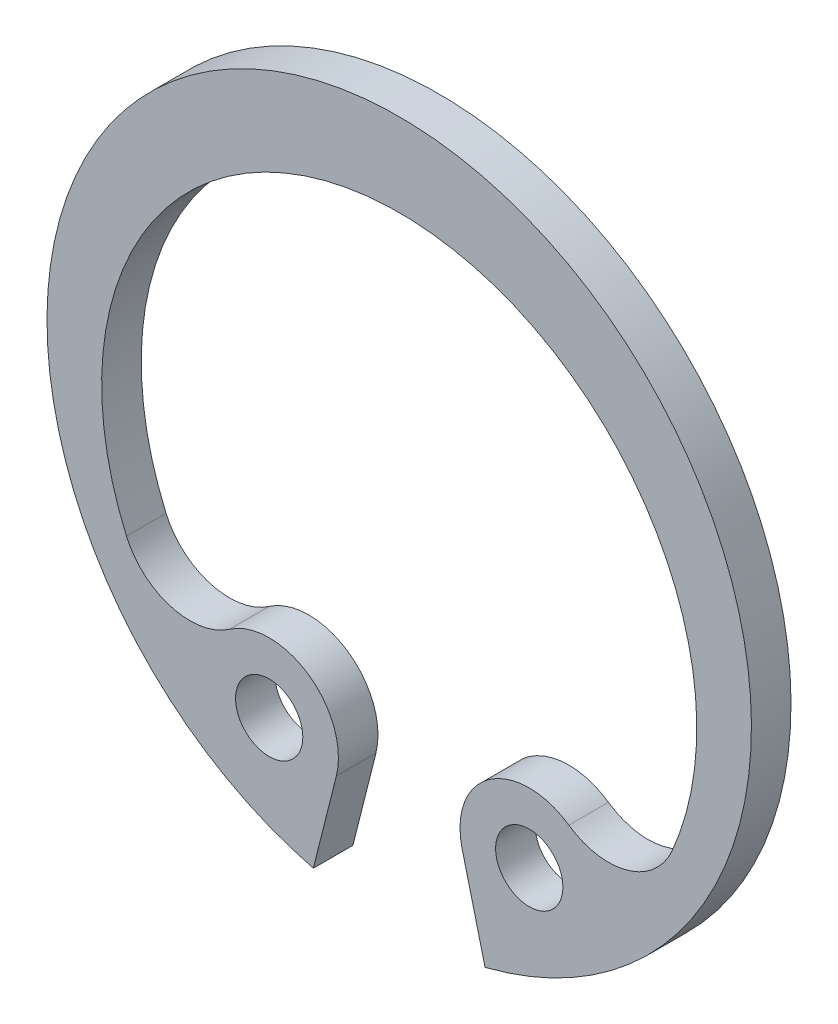
SolidWorks part; units mm, degrees
extrude "Body" add sketch "BodySke" against normal blind 1
sketch "BodySke" plane through (0, 0, 0) normal (0, 0, 1) x (1, 0, 0)
  line L0 (-1.5431, 0) -> (1.5431, 0) construction
  line L1 (0, 0) -> (0, 6.8) construction
  line L2 (2.1692, -8.6316) -> (1.5889, -6.3226)
  line L3 (-2.1692, -8.6316) -> (-1.5889, -6.3226)
  line L4 (0, 0) -> (7.7252, -4.4193) construction
  line L5 (0, 0) -> (-7.7252, -4.4193) construction
  line L6 (-3.079, -5.0717) -> (-3.4933, -6.7204) construction
  line L7 (3.1032, -5.1681) -> (3.4691, -6.624) construction
  arc A0 (-1.5889, -6.3226) -> (-4.2871, -4.4606) centre (-3.2861, -5.8961) ccw
  arc A1 (4.2871, -4.4606) -> (1.5889, -6.3226) centre (3.2861, -5.8961) ccw
  arc A2 (6.8138, -3.898) -> (-6.8138, -3.898) centre (0, -0.7189) ccw construction
  arc A3 (2.1692, -8.6316) -> (-2.1692, -8.6316) centre (0, 0) ccw
  circle A4 centre (3.2861, -5.8961) radius 0.85
  circle A5 centre (-3.2861, -5.8961) radius 0.85
  circle A6 centre (3.2861, -5.8961) radius 1.75 construction
  arc A7 (6.8921, -3.7246) -> (-6.8921, -3.7246) centre (0, -0.7189) ccw
  arc A8 (-3.2861, -5.8961) -> (3.2861, -5.8961) centre (0, 0) ccw construction
  arc A9 (-6.8921, -3.7246) -> (-4.2871, -4.4606) centre (-5.288, -3.0251) ccw
  arc A10 (4.2871, -4.4606) -> (6.8921, -3.7246) centre (5.288, -3.0251) ccw
  dimension "HoleDia" = 1.7
  dimension "HoleOffsetRad" = 6.75
  dimension "GrooveDia" = 17.8
  dimension "TipRad" = 1.75
  dimension "FilletRad" = 1.75
  dimension "LargeRad" = 6.8
  dimension "SmallRad" = 7.85
  dimension "SmallAngle" = 120.455
  dimension "GapAngle" = 28.213
material "1.0503 (C45)"
ref_plane "Plane1" through (0, 0, 0) normal (0, 0, 1) x (1, 0, 0)
ref_plane "Plane2" through (0, 0, 0) normal (0, 1, 0) x (1, 0, 0)
ref_plane "Plane3" through (0, 0, 0) normal (1, 0, 0) x (0, 0, -1)
other "Configuration Table"
sketch "Clipboard" plane through (0, 0, 0) normal (0, 0, 1) x (1, 0, 0)
  line L0 (0, 0) -> (2.1, 0)
  line L1 (0, 0) -> (0, 1.05)
  line L2 (0, 0) -> (0, -3.9)
  circle A0 centre (0, 0) radius 0.85
  circle A1 centre (0, 0) radius 8.5
  dimension "HoleDia" = 1.7
  dimension "BoreDia" = 17
  dimension "LargeSection" = 2.1
  dimension "SmallSection" = 1.05
  dimension "LugSection" = 3.9
sketch "ModLugSke" plane through (0, 0, 0) normal (0, 0, 1) x (1, 0, 0)
  line L0 (2.1692, -8.6316) -> (1.2428, -4.9453)
  line L1 (-2.1692, -8.6316) -> (-1.2428, -4.9453)
  line L2 (4.7664, -1.5106) -> (8.4841, -2.6888) construction
  line L3 (-4.7664, -1.5106) -> (-8.4841, -2.6888) construction
  line L4 (-2.1692, -8.6316) -> (-1.5889, -6.3226) construction
  line L5 (1.5889, -6.3226) -> (2.1692, -8.6316) construction
  line L6 (0, 0) -> (0, -18.0732) construction
  line L7 (7.3281, -2.3224) -> (8.4841, -2.6888)
  line L8 (-8.4841, -2.6888) -> (-7.3281, -2.3224)
  arc A0 (2.1692, -8.6316) -> (8.4841, -2.6888) centre (0, 0) ccw
  arc A1 (-3.2403, -3.808) -> (-1.3135, -4.8244) centre (0, 0) ccw
  arc A2 (2.1692, -8.6316) -> (-2.1692, -8.6316) centre (0, 0) ccw construction
  arc A3 (4.2871, -4.4606) -> (1.5889, -6.3226) centre (3.2861, -5.8961) ccw construction
  arc A4 (-3.2403, -3.808) -> (-3.3575, -3.799) centre (-3.3051, -3.8841) ccw
  arc A5 (-7.3281, -2.3224) -> (-3.3575, -3.799) centre (-4.7664, -1.5106) ccw
  arc A6 (6.8921, -3.7246) -> (-6.8921, -3.7246) centre (0, -0.7189) ccw construction
  arc A7 (3.3575, -3.799) -> (7.3281, -2.3224) centre (4.7664, -1.5106) ccw
  arc A8 (1.3135, -4.8244) -> (3.2403, -3.808) centre (0, 0) ccw
  arc A9 (-8.4841, -2.6888) -> (-2.1692, -8.6316) centre (0, 0) ccw
  circle A10 centre (-3.2861, -5.8961) radius 0.85
  circle A11 centre (-3.2861, -5.8961) radius 0.85 construction
  circle A12 centre (3.2861, -5.8961) radius 0.85
  circle A13 centre (3.2861, -5.8961) radius 0.85 construction
  arc A14 (-1.3135, -4.8244) -> (-1.2428, -4.9453) centre (-1.3398, -4.9209) cw
  arc A15 (1.3135, -4.8244) -> (1.2428, -4.9453) centre (1.3398, -4.9209) ccw
  arc A16 (3.2403, -3.808) -> (3.3575, -3.799) centre (3.3051, -3.8841) cw
  point P43 (1.2186, -4.8492)
  dimension "D1" = 0.1
extrude "ModLug" [suppressed] add sketch "ModLugSke" against normal through all
sketch "UnlSke" [suppressed] plane through (0, 0, 0) normal (0, 0, 1) x (1, 0, 0)
  line L0 (2.1178, -8.3352) -> (3.2259, -12.6966)
  line L1 (-2.1178, -8.3352) -> (-3.2259, -12.6966)
  line L2 (-3.2259, -12.6966) -> (-2.1422, -8.4315) construction
  line L3 (2.1422, -8.4315) -> (3.2259, -12.6966) construction
  arc A0 (2.1178, -8.3352) -> (-2.1178, -8.3352) centre (0, 0) ccw
  arc A1 (3.2259, -12.6966) -> (-3.2259, -12.6966) centre (0, 0) ccw
  arc A2 (3.2259, -12.6966) -> (-3.2259, -12.6966) centre (0, 0) ccw construction
  circle A4 centre (-4.4431, -9.5688) radius 1
  circle A5 centre (4.4431, -9.5688) radius 1
  circle A6 centre (4.4431, -9.5688) radius 1 construction
  circle A7 centre (-4.4431, -9.5688) radius 1 construction
  arc A8 (2.2134, -8.3103) -> (4.9183, -7.0548) centre (0, 0) ccw construction
extrude "Unlug" [suppressed] add sketch "UnlSke" against normal through all
equation "' \"BoreDia@Clipboard\" = 8"
equation "' \"Thickness@Body\" = 0.8"
equation "' \"GrooveDia@BodySke\" = 8.4"
equation "' \"LugSection@Clipboard\" = 2.4"
equation "' \"LargeSection@Clipboard\" = 1.1"
equation "' \"HoleDia@Clipboard\" = 1.0"
equation "' \"BoreDia@Clipboard\" = 25"
equation "' \"Thickness@Body\" = 1.2"
equation "' \"GrooveDia@BodySke\" = 26.2"
equation "' \"LugSection@Clipboard\" = 4.5"
equation "' \"LargeSection@Clipboard\" = 2.7"
equation "' \"HoleDia@Clipboard\" = 2"
equation "\"SmallSection@Clipboard\" = \"LargeSection@Clipboard\" * 0.5"
equation "\"TipRad@BodySke\" = (\"LugSection@Clipboard\" - (\"GrooveDia@BodySke\" / 2  -  \"BoreDia@Clipboard\" / 2 ) ) / 2"
equation "\"HoleOffsetRad@BodySke\" = (\"GrooveDia@BodySke\" / 2) - \"LugSection@Clipboard\"  + \"TipRad@BodySke\""
equation "\"LargeRad@BodySke\" =  \"GrooveDia@BodySke\" / 2 -  \"LargeSection@Clipboard\""
equation "\"SmallRad@BodySke\" =  \"GrooveDia@BodySke\" / 2 -  \"SmallSection@Clipboard\""
equation "\"HoleDia@BodySke\" =  \"HoleDia@Clipboard\""
equation "\"FilletRad@BodySke\" = \"TipRad@BodySke\" * 1.0"
equation "\"GapAngle@BodySke\" = 360 - 0.965 * 360 * ( \"BoreDia@Clipboard\" /  \"GrooveDia@BodySke\")"
equation "\"LugAng@ModLugSke\" = \"GapAngle@BodySke\"  + 2 * 360 * (\"LugSection@Clipboard\" / (\"BoreDia@Clipboard\" * 3.1416))"
